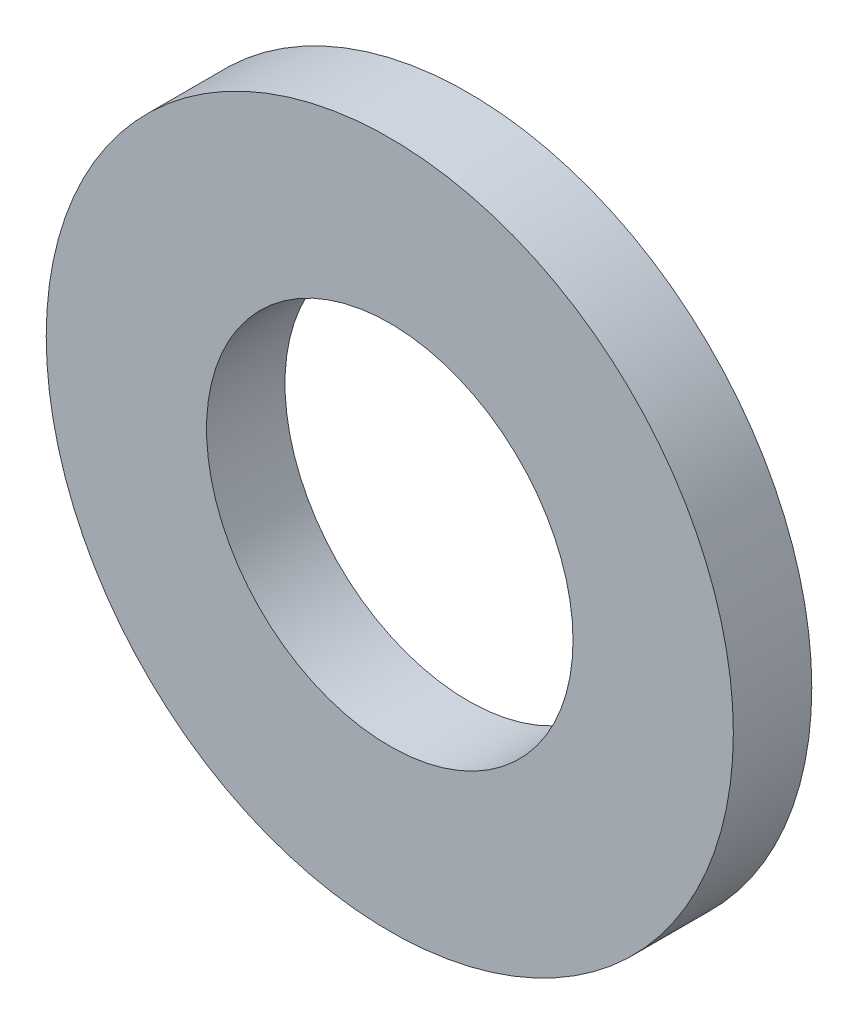
SolidWorks part; units mm, degrees
ref_plane "Front Plane" through (0, 0, 0) normal (0, 0, 1) x (1, 0, 0)
ref_plane "Top Plane" through (0, 0, 0) normal (0, 1, 0) x (1, 0, 0)
ref_plane "Right Plane" through (0, 0, 0) normal (1, 0, 0) x (0, 0, -1)
sketch "Sketch1" plane through (0, 0, 0) normal (0, 0, 1) x (1, 0, 0)
  circle A0 centre (0, 0) radius 3.2
  circle A1 centre (0, 0) radius 6
  dimension "ID" = 6.4
  dimension "OD" = 12
extrude "Extrude1" add sketch "Sketch1" against normal blind 1.37
